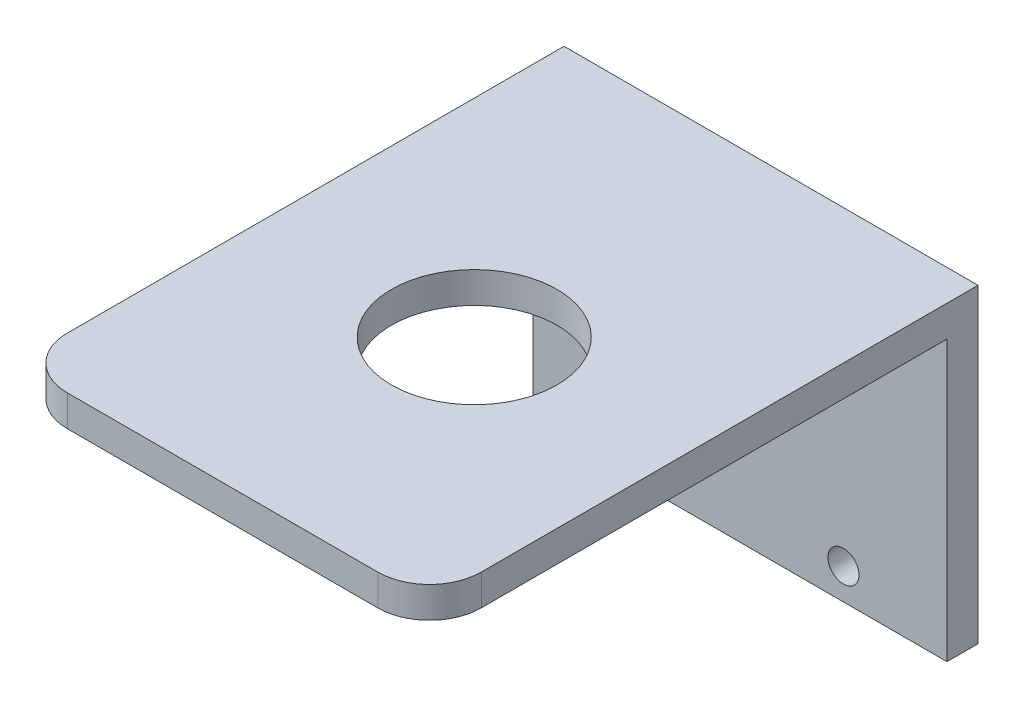
SolidWorks part; units mm, degrees
ref_plane "Front Plane" through (0, 0, 0) normal (0, 0, 1) x (1, 0, 0)
ref_plane "Top Plane" through (0, 0, 0) normal (0, 1, 0) x (1, 0, 0)
ref_plane "Right Plane" through (0, 0, 0) normal (1, 0, 0) x (0, 0, -1)
sketch "Sketch1" plane through (0, 0, 0) normal (0, 0, 1) x (1, 0, 0)
  line L1 (-20, 15) -> (20, 15)
  line L2 (-20, 15) -> (-20, -15)
  line L3 (-20, -15) -> (20, -15)
  line L4 (20, 15) -> (20, -15)
  line L5 (-20, 15) -> (20, -15) construction
  line L6 (-20, -15) -> (20, 15) construction
  circle A0 centre (-10, 8) radius 1.5
  circle A1 centre (10, 8) radius 1.5
  circle A2 centre (-10, -12) radius 1.5
  circle A3 centre (10, -12) radius 1.5
  point P0 (0, 0)
  dimension "D3" = 3
  dimension "D1" = 30
  dimension "D2" = 40
  dimension "D4" = 10
  dimension "D5" = 7
  dimension "D6" = 2
  dimension "D7" = 2
extrude "Boss-Extrude1" add sketch "Sketch1" along normal blind 3
sketch "Sketch2" plane through (0, 0, 3) normal (0, 0, 1) x (1, 0, 0)
  line L0 (20, -15) -> (20, 15) construction
  line L1 (-20, 15) -> (20, 15)
  line L2 (-20, 15) -> (-20, 12)
  line L3 (-20, 12) -> (20, 12)
  line L4 (20, 15) -> (20, 12)
  dimension "D1" = 3
extrude "Boss-Extrude2" add sketch "Sketch2" along normal blind 50
fillet "Fillet1" radius 5 2 edges at (-20, 13.5, 53) (20, 13.5, 53)
sketch "Sketch3" plane through (0, 15, 0) normal (0, 1, 0) x (1, 0, 0)
  circle A0 centre (0, -28.6811) radius 8
  dimension "D1" = 16
extrude "Cut-Extrude1" cut sketch "Sketch3" against normal up to surface (3 mm away) up to face at (-3.3333, 12, 42.5118)
